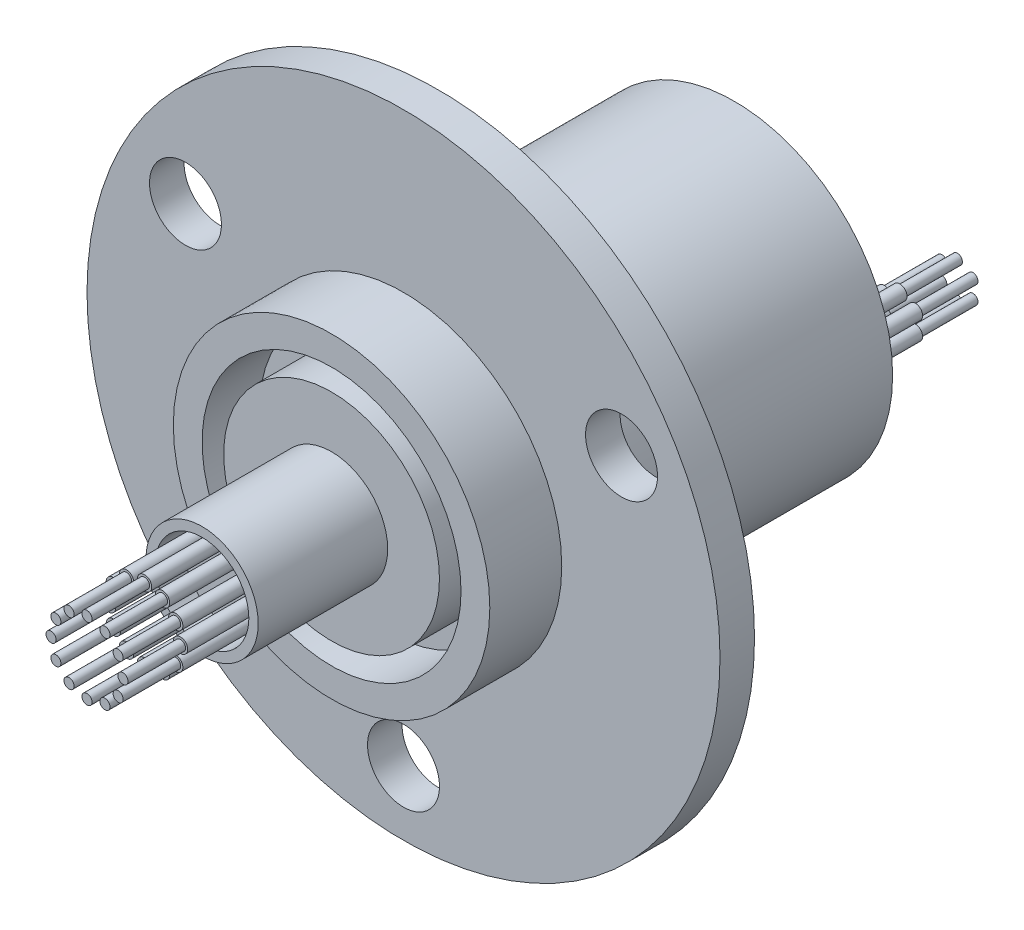
SolidWorks part; units mm, degrees
ref_plane "Ön Düzlem" through (0, 0, 0) normal (0, 0, 1) x (1, 0, 0)
ref_plane "Üst Düzlem" through (0, 0, 0) normal (0, 1, 0) x (1, 0, 0)
ref_plane "Sağ Düzlem" through (0, 0, 0) normal (1, 0, 0) x (0, 0, -1)
sketch "Çizim1" plane through (0, 0, 0) normal (0, 0, 1) x (1, 0, 0)
  circle A0 centre (0, 0) radius 11
  dimension "D1" = 22
extrude "Yükseklik-Ekstrüzyon1" add sketch "Çizim1" along normal blind 28
ref_plane "Düzlem1" through (0, 0, 23) normal (0, 0, 1) x (1, 0, 0)
sketch "Çizim2" plane through (0, 0, 23) normal (0, 0, 1) x (1, 0, 0)
  circle A0 centre (0, 0) radius 22
  dimension "D1" = 44
extrude "Yükseklik-Ekstrüzyon2" add sketch "Çizim2" against normal blind 2.4
sketch "Çizim3" plane through (0, 0, 23) normal (0, 0, 1) x (1, 0, 0)
  circle A0 centre (0, 0) radius 17.5 construction
  circle A1 centre (0, -17.5) radius 2.5
  circle A2 centre (-15.1554, 8.75) radius 2.5
  circle A3 centre (15.1554, 8.75) radius 2.5
  point P12 (0, 0)
  dimension "D1" = 35
  dimension "D2" = 5
  dimension "D3" = 3
extrude "Kes-Ekstrüzyon1" cut sketch "Çizim3" against normal blind 10
sketch "Çizim4" plane through (0, 0, 28) normal (0, 0, 1) x (1, 0, 0)
  circle A0 centre (0, 0) radius 3.9
  dimension "D1" = 7.8
extrude "Yükseklik-Ekstrüzyon3" add sketch "Çizim4" along normal blind 9
sketch "Çizim6" plane through (0, 0, 37) normal (0, 0, 1) x (1, 0, 0)
  circle A0 centre (0, 0) radius 3.25
  dimension "D1" = 6.5
extrude "Kes-Ekstrüzyon3" cut sketch "Çizim6" against normal blind 2
sketch "Çizim7" plane through (0, 0, 35) normal (0, 0, 1) x (1, 0, 0)
  circle A0 centre (0, 0) radius 2.5 construction
  circle A1 centre (0, 2.5) radius 0.5
  circle A2 centre (1.25, 2.1651) radius 0.5
  circle A3 centre (2.1651, 1.25) radius 0.5
  circle A4 centre (2.5, 0) radius 0.5
  circle A5 centre (2.1651, -1.25) radius 0.5
  circle A6 centre (1.25, -2.1651) radius 0.5
  circle A7 centre (0, -2.5) radius 0.5
  circle A8 centre (-1.25, -2.1651) radius 0.5
  circle A9 centre (-2.1651, -1.25) radius 0.5
  circle A10 centre (-2.5, 0) radius 0.5
  circle A11 centre (-2.1651, 1.25) radius 0.5
  circle A12 centre (-1.25, 2.1651) radius 0.5
  point P30 (0, 0)
  dimension "D1" = 5
  dimension "D2" = 1
  dimension "D3" = 12
extrude "Yükseklik-Ekstrüzyon5" add sketch "Çizim7" along normal blind 6
sketch "Çizim8" plane through (0, 0, 41) normal (0, 0, 1) x (1, 0, 0)
  circle A0 centre (0, 0) radius 2.5 construction
  circle A1 centre (0, 2.5) radius 0.35
  circle A2 centre (1.25, 2.1651) radius 0.35
  circle A3 centre (2.1651, 1.25) radius 0.35
  circle A4 centre (2.5, 0) radius 0.35
  circle A5 centre (2.1651, -1.25) radius 0.35
  circle A6 centre (1.25, -2.1651) radius 0.35
  circle A7 centre (0, -2.5) radius 0.35
  circle A8 centre (-1.25, -2.1651) radius 0.35
  circle A9 centre (-2.1651, -1.25) radius 0.35
  circle A10 centre (-2.5, 0) radius 0.35
  circle A11 centre (-2.1651, 1.25) radius 0.35
  circle A12 centre (-1.25, 2.1651) radius 0.35
  point P30 (0, 0)
  dimension "D1" = 0.7
  dimension "D2" = 12
extrude "Yükseklik-Ekstrüzyon6" add sketch "Çizim8" along normal blind 4
sketch "Çizim9" plane through (0, 0, 0) normal (0, 0, -1) x (-1, 0, 0)
  line L0 (9.1568, 0) -> (-16.4098, 0) construction
  circle A0 centre (-7.5, 0) radius 2
  circle A1 centre (7.5, 0) radius 2
  dimension "D1" = 4
  dimension "D2" = 4
  dimension "D3" = 15
  dimension "D4" = 7.5
extrude "Kes-Ekstrüzyon4" cut sketch "Çizim9" against normal blind 2
sketch "Çizim10" plane through (0, 0, 2) normal (0, 0, -1) x (-1, 0, 0)
  line L0 (0, 9.2475) -> (0, -8.8848) construction
  circle A0 centre (7.5, 0) radius 1.25 construction
  circle A1 centre (7.5, 1.25) radius 0.5
  circle A2 centre (8.5825, 0.625) radius 0.5
  circle A3 centre (8.5825, -0.625) radius 0.5
  circle A4 centre (7.5, -1.25) radius 0.5
  circle A5 centre (-7.5, 0) radius 1.25 construction
  circle A6 centre (-6.4175, 0.625) radius 0.5
  circle A7 centre (-6.4175, -0.625) radius 0.5
  circle A8 centre (-7.5, -1.25) radius 0.5
  circle A9 centre (-8.5825, -0.625) radius 0.5
  circle A10 centre (6.4175, -0.625) radius 0.5
  circle A11 centre (6.4175, 0.625) radius 0.5
  circle A12 centre (-8.5825, 0.625) radius 0.5
  circle A13 centre (-7.5, 1.25) radius 0.5
  point P14 (7.5, 0)
  point P32 (7.5, 0)
  dimension "D1" = 2.5
  dimension "D2" = 1
  dimension "D3" = 6
extrude "Yükseklik-Ekstrüzyon7" add sketch "Çizim10" along normal blind 6
sketch "Çizim12" plane through (0, 0, 28) normal (0, 0, 1) x (1, 0, 0)
  circle A0 centre (0, 0) radius 9
  circle A1 centre (0, 0) radius 7.5
  dimension "D1" = 18
  dimension "D2" = 15
extrude "Kes-Ekstrüzyon5" cut sketch "Çizim12" against normal blind 4
sketch "Çizim13" plane through (0, 0, -4) normal (0, 0, -1) x (-1, 0, 0)
  line L0 (0, 0) -> (0, 3.4175) construction
  circle A0 centre (7.5, 1.25) radius 0.35
  circle A1 centre (8.5825, 0.625) radius 0.35
  circle A2 centre (8.5825, -0.625) radius 0.35
  circle A3 centre (7.5, -1.25) radius 0.35
  circle A4 centre (6.4175, -0.625) radius 0.35
  circle A5 centre (6.4175, 0.625) radius 0.35
  circle A6 centre (-6.4175, 0.625) radius 0.35
  circle A7 centre (-6.4175, -0.625) radius 0.35
  circle A8 centre (-7.5, -1.25) radius 0.35
  circle A9 centre (-8.5825, -0.625) radius 0.35
  circle A10 centre (-8.5825, 0.625) radius 0.35
  circle A11 centre (-7.5, 1.25) radius 0.35
  point P16 (7.5, 0)
  point P29 (-7.5, 0)
  dimension "D1" = 0.7
  dimension "D2" = 6
extrude "Yükseklik-Ekstrüzyon8" add sketch "Çizim13" along normal blind 4
